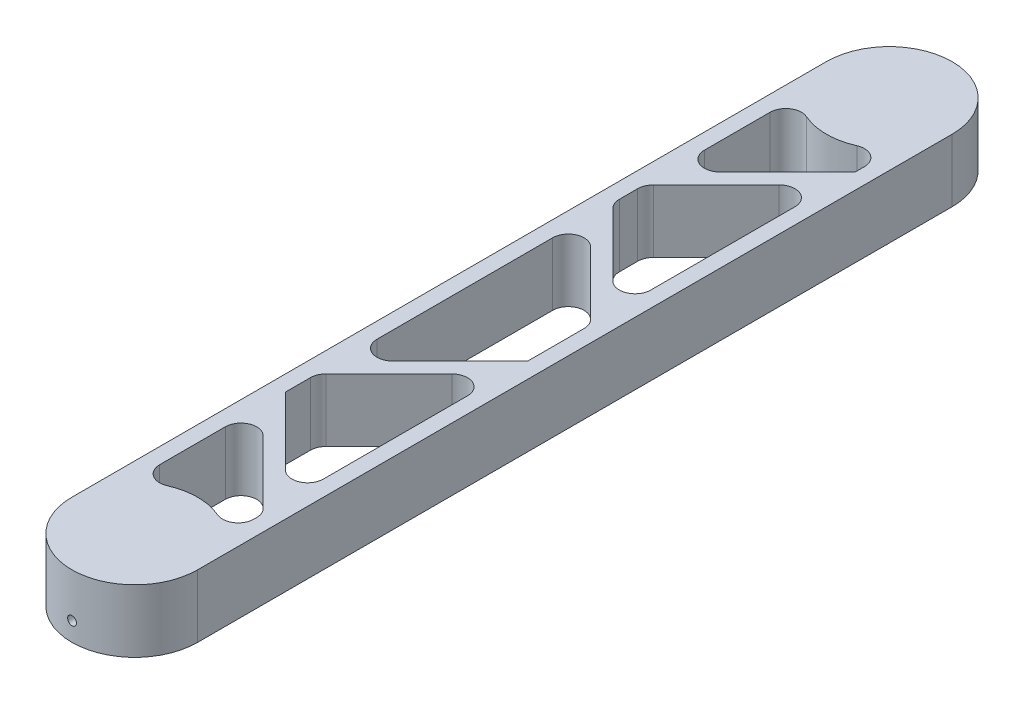
SolidWorks part; units mm, degrees
ref_plane "Front Plane" through (0, 0, 0) normal (0, 0, 1) x (1, 0, 0)
ref_plane "Top Plane" through (0, 0, 0) normal (0, 1, 0) x (1, 0, 0)
ref_plane "Right Plane" through (0, 0, 0) normal (1, 0, 0) x (0, 0, -1)
sketch "Sketch1" plane through (0, 0, 0) normal (0, 1, 0) x (1, 0, 0)
  circle A0 centre (0, 0) radius 12.7
  dimension "D1" = 25.4
extrude "Boss-Extrude1" add sketch "Sketch1" along normal blind 12.7
sketch "Sketch2" plane through (0, 0, 0) normal (0, -1, 0) x (1, 0, 0)
  circle A0 centre (0, 0) radius 1.6256
  dimension "D1" = 3.2512
extrude "Cut-Extrude1" cut sketch "Sketch2" against normal blind 9.525
sketch "Sketch3" plane through (0, 0, 0) normal (0, -1, 0) x (1, 0, 0)
  circle A0 centre (0, 0) radius 9.525
  dimension "D1" = 19.05
extrude "Cut-Extrude2" cut sketch "Sketch3" against normal blind 2.54 contours A0
hole_wizard "#2-56 Tapped Hole1" positions "Sketch6" profile "Sketch5" tap size "#2-56" standard "ANSI Inch"
sketch "Sketch6" plane through (0, 0, 0) normal (0, 0, 1) x (1, 0, 0)
  line L1 (-1.6256, 2.54) -> (1.6256, 2.54) construction
  point P0 (0, 3.81)
  dimension "D1" = 1.27
sketch "Sketch5" plane through (0, 3.81, 0) normal (1, 0, 0) x (0, 1, 0)
  line L0 (0, 0) -> (0, 13.7422)
  line L1 (0, 13.7422) -> (0.889, 13.208)
  line L2 (0.889, 13.208) -> (0.889, 0)
  line L5 (0.889, 0) -> (0, 0)
  line L10 (0, 13.7422) -> (-0.889, 13.208) construction
  line L11 (0, -6.35) -> (0, 107.95) construction
  dimension "Tap Drill Dia." = 1.778
  dimension "Tap Drill Depth" = 13.208
  dimension "Drill Angle" = 118
sketch "Sketch7" plane through (0, 12.7, 0) normal (0, 1, 0) x (1, 0, 0)
  line L0 (-12.7, 0) -> (-12.7, 152.4)
  line L1 (12.7, 0) -> (12.7, 152.4)
  circle A0 centre (0, 0) radius 12.7 construction
  arc A1 (-12.7, 152.4) -> (12.7, 152.4) centre (0, 152.4) cw
  arc A2 (-12.7, 0) -> (12.7, 0) centre (0, 0) cw
  circle M1 centre (0, 0) radius 12.7
  dimension "D3" = 12.7
  dimension "D1" = 152.4
  dimension "D2" = 152.4
extrude "Boss-Extrude2" add sketch "Sketch7" against normal up to surface (12.7 mm away) contours A1 L0 L1 M1 up to face at (0, 0, -9.525)
sketch "Sketch10" plane through (0, 0, 0) normal (0, -1, 0) x (1, 0, 0)
  circle A0 centre (0, -152.4) radius 1.651
  dimension "D1" = 3.302
extrude "Cut-Extrude4" cut sketch "Sketch10" against normal up to surface (9.525 mm away) up to face at (0, 9.525, -1.6256)
sketch "Sketch11" plane through (0, 0, 0) normal (0, -1, 0) x (1, 0, 0)
  circle A0 centre (0, -152.4) radius 9.525
  dimension "D1" = 19.05
extrude "Cut-Extrude5" cut sketch "Sketch11" against normal up to surface (2.54 mm away) up to face at (0, 2.54, -9.525)
ref_plane "Plane1" through (0, 0, -152.4) normal (0, 0, -1) x (-1, 0, 0)
hole_wizard "#2-56 Tapped Hole2" positions "Sketch13" profile "Sketch14" tap size "#2-56" standard "ANSI Inch"
sketch "Sketch13" plane through (0, 0, -152.4) normal (0, 0, -1) x (-1, 0, 0)
  line L0 (12.7, 0) -> (12.7, 12.7) construction
  point P0 (0, 3.81)
  dimension "D1" = 12.7
  dimension "D2" = 3.81
sketch "Sketch14" plane through (0, 3.81, -152.4) normal (1, 0, 0) x (0, -1, 0)
  line L0 (0, 0) -> (0, 13.7422)
  line L1 (0, 13.7422) -> (0.889, 13.208)
  line L2 (0.889, 13.208) -> (0.889, 0)
  line L5 (0.889, 0) -> (0, 0)
  line L10 (0, 13.7422) -> (-0.889, 13.208) construction
  line L11 (0, -6.35) -> (0, 107.95) construction
  dimension "Tap Drill Dia." = 1.778
  dimension "Tap Drill Depth" = 13.208
  dimension "Drill Angle" = 118
sketch "Sketch15" plane through (0, 0, 0) normal (0, -1, 0) x (1, 0, 0)
  line L0 (12.7, -76.2) -> (-12.7, -76.2) construction
  line L1 (12.7, -152.4) -> (12.7, 0) construction
  line L2 (-12.7, -152.4) -> (-12.7, 0) construction
  line L3 (-9.525, 0) -> (-9.525, -152.4)
  line L4 (9.525, 0) -> (9.525, -152.4)
  line L5 (9.525, -69.85) -> (-9.525, -50.8)
  line L6 (-9.525, -50.8) -> (-9.525, -46.3099)
  line L7 (-9.525, -46.3099) -> (9.525, -65.3599)
  line L8 (-9.525, -39.9599) -> (9.525, -20.9099)
  line L9 (9.525, -20.9099) -> (9.525, -16.4197)
  line L10 (9.525, -16.4197) -> (-9.525, -35.4697)
  line L11 (9.525, -82.55) -> (-9.525, -101.6)
  line L12 (-9.525, -101.6) -> (-9.525, -106.0901)
  line L13 (-9.525, -106.0901) -> (9.525, -87.0401)
  line L14 (-9.525, -112.4401) -> (9.525, -131.4901)
  line L15 (9.525, -131.4901) -> (9.525, -135.9803)
  line L16 (9.525, -135.9803) -> (-9.525, -116.9303)
  circle A0 centre (0, 0) radius 12.7
  circle A1 centre (0, -152.4) radius 12.7
  circle A2 centre (0, 0) radius 9.525 construction
  circle A3 centre (0, -152.4) radius 9.525 construction
  dimension "D1" = 25.4
  dimension "D2" = 3.175
  dimension "D3" = 3.175
  dimension "D4" = 3.175
  dimension "D5" = 3.175
  dimension "D6" = 3.175
  dimension "D7" = 3.175
  dimension "D8" = 6.35
  dimension "D9" = 6.35
  dimension "D10" = 6.35
  dimension "D11" = 45
  dimension "D12" = 45
  dimension "D13" = 45
  dimension "D14" = 45
  dimension "D15" = 6.35
extrude "Cut-Extrude6" cut sketch "Sketch15" against normal up to surface (12.7 mm away) contours A0 L3 L10 L4 | L8 L3 L7 L4 | L0 L4 L5 L3 | L4 L0 L3 L11 | L3 L14 L4 L13 | A1 L4 L16 L3 up to face at (0, 12.7, -76.2)
fillet "Fillet1" radius 3.175 17 edges at (-9.525, 6.35, -8.4003) (9.525, 6.35, -8.4003) (-9.525, 6.35, -143.9997) (-9.525, 6.35, -116.9303) (9.525, 6.35, -143.9997) (9.525, 6.35, -131.4901) (9.525, 6.35, -87.0401) (-9.525, 6.35, -106.0901) (-9.525, 6.35, -112.4401) (-9.525, 6.35, -101.6) (9.525, 6.35, -82.55) (-9.525, 6.35, -50.8) (9.525, 6.35, -65.3599) (9.525, 6.35, -20.9099) (-9.525, 6.35, -46.3099) (-9.525, 6.35, -35.4697) (9.525, 6.35, -16.4197)
